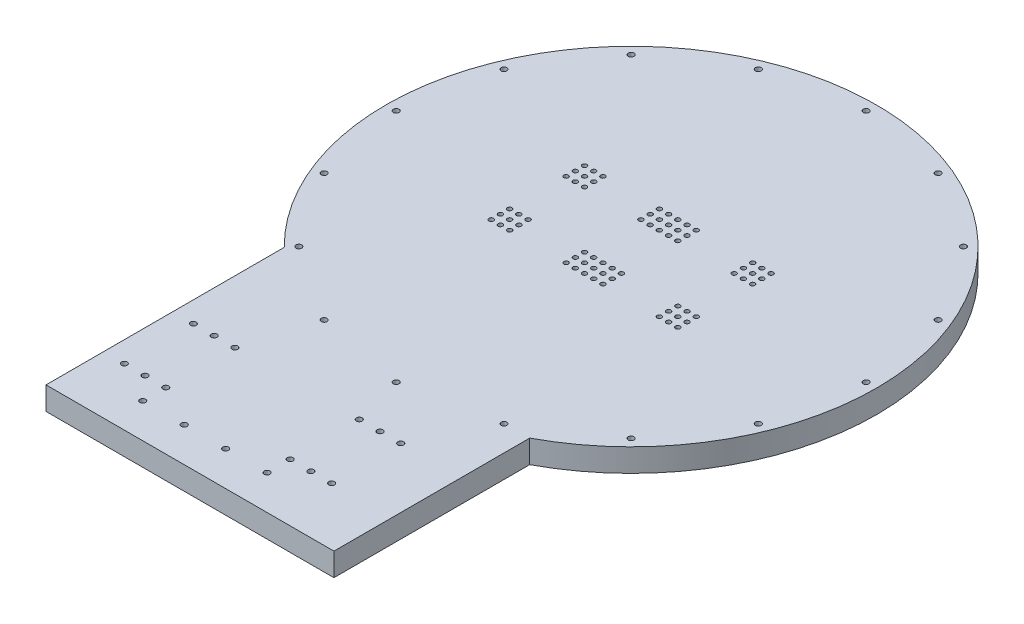
SolidWorks part; units mm, degrees
ref_plane "前视基准面" through (0, 0, 0) normal (0, 0, 1) x (1, 0, 0)
ref_plane "上视基准面" through (0, 0, 0) normal (0, 1, 0) x (1, 0, 0)
ref_plane "右视基准面" through (0, 0, 0) normal (1, 0, 0) x (0, 0, -1)
sketch "草图1" plane through (0, 0, 0) normal (0, 1, 0) x (1, 0, 0)
  circle A0 centre (0, 0) radius 195
  dimension "D1" = 390
extrude "凸台-拉伸1" add sketch "草图1" along normal blind 20
sketch "草图2" plane through (0, 20, 0) normal (0, 1, 0) x (1, 0, 0)
  line L0 (0, 0) -> (0, 15)
  line L1 (0, 15) -> (8, 15)
  line L2 (8, 15) -> (-8, 15)
  line L3 (-8, 15) -> (-8, 0)
  line L4 (8, 15) -> (8, 0)
  line L5 (-8, 32.5) -> (-8, -32.5)
  line L6 (-169.2909, 0) -> (169.2909, 0)
  line L7 (-8, 32.5) -> (-73, 32.5)
  line L8 (-8, 32.5) -> (-8, -32.5)
  line L9 (8, -32.5) -> (8, 32.5)
  line L10 (-8, -32.5) -> (-73, -32.5)
  line L11 (8, 32.5) -> (73, 32.5)
  line L12 (8, 32.5) -> (8, -32.5)
  line L13 (8, -32.5) -> (73, -32.5)
  line L14 (73, 32.5) -> (73, -32.5)
  line L15 (-73, 32.5) -> (-73, -32.5)
  line L16 (0, 158.5873) -> (0, -158.5873)
  circle A0 centre (-73, 32.5) radius 2
  circle A1 centre (-8, 32.5) radius 2
  circle A2 centre (-73, -32.5) radius 2
  circle A3 centre (-8, -32.5) radius 2
  circle A4 centre (8, 32.5) radius 2
  circle A5 centre (8, -32.5) radius 2
  circle A6 centre (73, -32.5) radius 2
  circle A7 centre (73, 32.5) radius 2
  point P8 (-8, 15)
  point P14 (8, 0)
  point P16 (-8, 0)
  point P29 (0, 0)
  point P32 (0, 0)
  dimension "D9" = 4
  dimension "D10" = 4
  dimension "D11" = 4
  dimension "D12" = 4
  dimension "D13" = 65
  dimension "D14" = 4
  dimension "D15" = 4
  dimension "D16" = 4
  dimension "D17" = 4
  dimension "D1" = 15
  dimension "D2" = 8
  dimension "D3" = 16
  dimension "D4" = 15
  dimension "D5" = 65
  dimension "D6" = 15
  dimension "D7" = 65
  dimension "D8" = 65
hole_wizard "M4 螺纹孔1" positions "3D草图2" profile "草图25" tap size "M4" standard "ISO"
sketch3d "3D草图2"
  point P0 (-73, 20, -32.5)
  point P3 (-73, 20, 32.5)
  point P6 (-8, 20, 32.5)
  point P9 (8, 20, 32.5)
  point P12 (-8, 20, -32.5)
  point P15 (8, 20, -32.5)
  point P18 (73, 20, -32.5)
  point P21 (73, 20, 32.5)
sketch "草图25" plane through (-73, 20, -32.5) normal (1, 0, 0) x (0, 0, 1)
  line L0 (0, 0) -> (0, 11.2017)
  line L1 (0, 11.2017) -> (2, 10)
  line L2 (2, 10) -> (2, 0)
  line L5 (2, 0) -> (0, 0)
  line L10 (0, 11.2017) -> (-2, 10) construction
  line L11 (0, -6.35) -> (0, 107.95) construction
  dimension "螺纹孔钻头直径" = 4
  dimension "螺纹孔钻头深度" = 10
  dimension "导头角度" = 118
cosmetic thread "孔螺蚊线2" parameters "D1"=9.5, "D2"=4
cosmetic thread "孔螺蚊线3" parameters "D1"=9.5, "D2"=4
cosmetic thread "孔螺蚊线4" parameters "D1"=9.5, "D2"=4
cosmetic thread "孔螺蚊线5" parameters "D1"=9.5, "D2"=4
cosmetic thread "孔螺蚊线6" parameters "D1"=9.5, "D2"=4
cosmetic thread "孔螺蚊线7" parameters "D1"=9.5, "D2"=4
cosmetic thread "孔螺蚊线8" parameters "D1"=9.5, "D2"=4
cosmetic thread "孔螺蚊线9" parameters "D1"=9.5, "D2"=4
pattern_linear "阵列(线性)2" count 2 spacing 8 along (-1, 0, 0) count 2 spacing 8 along (0, 0, 1) of "M4 螺纹孔1"
pattern_linear "阵列(线性)3" count 2 spacing 8 along (1, 0, 0) count 2 spacing 8 along (0, 0, -1) of "M4 螺纹孔1"
pattern_linear "阵列(线性)4" count 2 spacing 8 along (1, 0, 0) count 2 spacing 8 along (0, 0, 1) of "M4 螺纹孔1"
pattern_linear "阵列(线性)5" count 2 spacing 8 along (-1, 0, 0) count 2 spacing 8 along (0, 0, -1) of "M4 螺纹孔1"
sketch "草图3" plane through (0, 20, 0) normal (0, 1, 0) x (1, 0, 0)
  circle A0 centre (0, 0) radius 213
  circle A1 centre (0, 0) radius 204
  circle A2 centre (0, 204) radius 3
  circle A3 centre (78.0674, 188.4714) radius 3
  circle A4 centre (0, 0) radius 204
  circle A5 centre (144.2498, 144.2498) radius 3
  circle A6 centre (0, 0) radius 204
  circle A7 centre (188.4714, 78.0674) radius 3
  circle A8 centre (0, 0) radius 204
  circle A9 centre (204, 0) radius 3
  circle A10 centre (0, 0) radius 204
  circle A11 centre (188.4714, -78.0674) radius 3
  circle A12 centre (0, 0) radius 204
  circle A13 centre (144.2498, -144.2498) radius 3
  circle A14 centre (0, 0) radius 204
  circle A15 centre (78.0674, -188.4714) radius 3
  circle A16 centre (0, 0) radius 204
  circle A17 centre (0, -204) radius 3
  circle A18 centre (0, 0) radius 204
  circle A19 centre (-78.0674, -188.4714) radius 3
  circle A20 centre (0, 0) radius 204
  circle A21 centre (-144.2498, -144.2498) radius 3
  circle A22 centre (0, 0) radius 204
  circle A23 centre (-188.4714, -78.0674) radius 3
  circle A24 centre (0, 0) radius 204
  circle A25 centre (-204, 0) radius 3
  circle A26 centre (0, 0) radius 204
  circle A27 centre (-188.4714, 78.0674) radius 3
  circle A28 centre (0, 0) radius 204
  circle A29 centre (-144.2498, 144.2498) radius 3
  circle A30 centre (0, 0) radius 204
  circle A31 centre (-78.0674, 188.4714) radius 3
  circle A32 centre (0, 0) radius 204
  circle A33 centre (0, 0) radius 195
  circle A34 centre (0, 0) radius 204
  circle A36 centre (0, 0) radius 204
  circle A38 centre (0, 0) radius 204
  circle A40 centre (0, 0) radius 204
  circle A42 centre (0, 0) radius 204
  circle A44 centre (0, 0) radius 204
  circle A46 centre (0, 0) radius 204
  circle A48 centre (0, 0) radius 204
  circle A50 centre (0, 0) radius 204
  circle A52 centre (0, 0) radius 204
  circle A54 centre (0, 0) radius 204
  circle A56 centre (0, 0) radius 204
  circle A58 centre (0, 0) radius 204
  circle A60 centre (0, 0) radius 204
  circle A62 centre (0, 0) radius 204
  circle A64 centre (0, 0) radius 204
  circle A66 centre (0, 0) radius 204
  circle A68 centre (0, 0) radius 204
  circle A70 centre (0, 0) radius 204
  circle A72 centre (0, 0) radius 204
  circle A73 centre (35.4242, 200.9008) radius 3 [skipped]
  circle A74 centre (69.7721, 191.6973) radius 3 [skipped]
  circle A75 centre (102, 176.6692) radius 3 [skipped]
  circle A76 centre (131.1287, 156.2731) radius 3 [skipped]
  circle A77 centre (156.2731, 131.1287) radius 3 [skipped]
  circle A78 centre (176.6692, 102) radius 3 [skipped]
  circle A79 centre (-35.4242, -200.9008) radius 3 [skipped]
  circle A80 centre (0, -204) radius 3 [skipped]
  circle A81 centre (35.4242, -200.9008) radius 3 [skipped]
  circle A82 centre (69.7721, -191.6973) radius 3 [skipped]
  circle A83 centre (102, -176.6692) radius 3 [skipped]
  circle A84 centre (131.1287, -156.2731) radius 3 [skipped]
  circle A85 centre (156.2731, -131.1287) radius 3 [skipped]
  circle A86 centre (176.6692, -102) radius 3 [skipped]
  circle A87 centre (191.6973, 69.7721) radius 3 [skipped]
  circle A88 centre (200.9008, 35.4242) radius 3 [skipped]
  circle A89 centre (204, 0) radius 3 [skipped]
  circle A90 centre (200.9008, -35.4242) radius 3 [skipped]
  circle A91 centre (191.6973, -69.7721) radius 3 [skipped]
  circle A92 centre (-69.7721, -191.6973) radius 3 [skipped]
  circle A93 centre (-102, -176.6692) radius 3 [skipped]
  circle A94 centre (-131.1287, -156.2731) radius 3 [skipped]
  circle A95 centre (-156.2731, -131.1287) radius 3 [skipped]
  circle A96 centre (-176.6692, -102) radius 3 [skipped]
  circle A97 centre (-191.6973, -69.7721) radius 3 [skipped]
  circle A98 centre (-200.9008, -35.4242) radius 3 [skipped]
  circle A99 centre (-204, 0) radius 3 [skipped]
  circle A100 centre (-200.9008, 35.4242) radius 3 [skipped]
  circle A101 centre (-191.6973, 69.7721) radius 3 [skipped]
  circle A102 centre (-176.6692, 102) radius 3 [skipped]
  circle A103 centre (-156.2731, 131.1287) radius 3 [skipped]
  circle A104 centre (-131.1287, 156.2731) radius 3 [skipped]
  circle A105 centre (-102, 176.6692) radius 3 [skipped]
  circle A106 centre (-69.7721, 191.6973) radius 3 [skipped]
  circle A107 centre (-35.4242, 200.9008) radius 3 [skipped]
  point P55 (0, 0)
  point P114 (0, 0)
  dimension "D1" = 426
  dimension "D2" = 408
  dimension "D3" = 6
  dimension "D4" = 36
  dimension "D5" = 16
extrude "凸台-拉伸2" add sketch "草图3" against normal blind 20
sketch "草图9" plane through (0, 0, 0) normal (0, -1, 0) x (1, 0, 0)
  line L5 (0, 0) -> (0, 262.5812) construction
  line L6 (-100, 210.4048) -> (100, 210.4048) construction
  line L7 (100, 210.4048) -> (100, 188.0665) construction
  line L8 (100, 188.0665) -> (100, 338.0665)
  line L9 (100, 338.0665) -> (-100, 338.0665)
  line L10 (-100, 338.0665) -> (-100, 188.0665)
  arc A0 (-100, 188.0665) -> (100, 188.0665) centre (0, -24.5952) cw
  circle A1 centre (0, 0) radius 213 construction
  point P7 (-209.55, 0)
  point P18 (0, 210.4048)
  dimension "D1" = 235
  dimension "D4" = 200
  dimension "D5" = 150
  dimension "D6" = 150
  dimension "D7" = 200
extrude "凸台-拉伸3" add sketch "草图9" against normal blind 20
sketch "草图14" plane through (0, 20, 0) normal (0, 1, 0) x (1, 0, 0)
  line L0 (-100, -338.0665) -> (-150, -338.0665)
  line L1 (-150, -338.0665) -> (-150, -151.225)
  line L2 (-100, -338.0665) -> (-100, -188.0665)
  arc A0 (100, -188.0665) -> (-100, -188.0665) centre (0, 0) ccw construction
  arc A1 (-100, -188.0665) -> (-150, -151.225) centre (13.1778, 17.8845) cw
  dimension "D2" = 235
  dimension "D1" = 50
extrude "凸台-拉伸4" add sketch "草图14" against normal blind 20
sketch "草图23" plane through (0, 0, 338.0665) normal (0, 0, 1) x (1, 0, 0)
  line L1 (-150, 20) -> (100, 20)
  line L2 (-150, 20) -> (-150, 0)
  line L3 (-150, 0) -> (100, 0)
  line L4 (100, 20) -> (100, 0)
extrude "凸台-拉伸5" add sketch "草图23" along normal blind 20
sketch "草图21" plane through (0, 20, 0) normal (0, 1, 0) x (1, 0, 0)
  line L0 (0, 0) -> (0, -252)
  dimension "D1" = 252
sketch "草图22" plane through (0, 20, 0) normal (0, 1, 0) x (1, 0, 0)
  line L0 (0, -252) -> (-102, -252)
  line L1 (0, -252) -> (12, -252)
  line L2 (17.5, -347) -> (-107.5, -347)
  line L3 (-102, -252) -> (12, -252)
  line L4 (-102, -252) -> (-102, -347)
  line L5 (-102, -347) -> (12, -347)
  line L6 (12, -252) -> (12, -347)
  line L7 (17.5, -347) -> (17.5, -362)
  line L8 (17.5, -362) -> (67.5, -362)
  circle A0 centre (67.5, -362) radius 3
  circle A1 centre (42.5, -362) radius 3
  circle A2 centre (17.5, -362) radius 3
  circle A3 centre (-7.5, -362) radius 3
  circle A4 centre (-32.5, -362) radius 3
  circle A5 centre (-57.5, -362) radius 3
  circle A6 centre (-82.5, -362) radius 3
  circle A7 centre (-107.5, -362) radius 3
  circle A8 centre (-132.5, -362) radius 3
  circle A9 centre (42.5, -337) radius 3
  circle A10 centre (17.5, -337) radius 3
  circle A11 centre (-7.5, -337) radius 3
  circle A12 centre (-32.5, -337) radius 3
  circle A13 centre (-57.5, -337) radius 3
  circle A14 centre (-82.5, -337) radius 3
  circle A15 centre (-107.5, -337) radius 3
  circle A16 centre (-132.5, -337) radius 3
  circle A17 centre (42.5, -312) radius 3
  circle A18 centre (17.5, -312) radius 3
  circle A19 centre (-7.5, -312) radius 3
  circle A20 centre (-32.5, -312) radius 3
  circle A21 centre (-57.5, -312) radius 3
  circle A22 centre (-82.5, -312) radius 3
  circle A23 centre (-107.5, -312) radius 3
  circle A24 centre (-132.5, -312) radius 3
  circle A25 centre (42.5, -287) radius 3
  circle A26 centre (17.5, -287) radius 3
  circle A27 centre (-7.5, -287) radius 3
  circle A28 centre (-32.5, -287) radius 3
  circle A29 centre (-57.5, -287) radius 3
  circle A30 centre (-82.5, -287) radius 3
  circle A31 centre (-107.5, -287) radius 3
  circle A32 centre (-132.5, -287) radius 3
  circle A33 centre (42.5, -262) radius 3
  circle A34 centre (17.5, -262) radius 3
  circle A35 centre (-7.5, -262) radius 3
  circle A36 centre (-32.5, -262) radius 3
  circle A37 centre (-57.5, -262) radius 3
  circle A38 centre (-82.5, -262) radius 3
  circle A39 centre (-107.5, -262) radius 3
  circle A40 centre (-132.5, -262) radius 3
  circle A41 centre (42.5, -237) radius 3
  circle A42 centre (17.5, -237) radius 3
  circle A43 centre (-7.5, -237) radius 3
  circle A44 centre (-32.5, -237) radius 3
  circle A45 centre (-57.5, -237) radius 3
  circle A46 centre (-82.5, -237) radius 3
  circle A47 centre (-107.5, -237) radius 3
  circle A48 centre (-132.5, -237) radius 3
  circle A49 centre (67.5, -337) radius 3
  circle A50 centre (67.5, -312) radius 3
  circle A51 centre (67.5, -287) radius 3
  circle A52 centre (67.5, -262) radius 3
  circle A53 centre (67.5, -237) radius 3
  point P9 (-45, -347)
  dimension "D6" = 50
  dimension "D7" = 6
  dimension "D1" = 102
  dimension "D2" = 12
  dimension "D3" = 95
  dimension "D4" = 125
  dimension "D5" = 15
  dimension "D8" = 9
  dimension "D9" = 6
sketch "草图31" plane through (0, 20, 0) normal (0, 1, 0) x (1, 0, 0)
  line L0 (0, 0) -> (0, 204)
  circle A0 centre (0, 0) radius 204
  dimension "D1" = 408
hole_wizard "M6 螺纹孔3" positions "3D草图4" profile "草图32" tap size "M6" standard "ISO" end condition through all
sketch3d "3D草图4"
  point P0 (0, 20, -204)
sketch "草图32" plane through (0, 20, -204) normal (1, 0, 0) x (0, 0, 1)
  line L0 (0, 0) -> (0, 20)
  line L1 (0, 20) -> (2.5, 20)
  line L2 (2.5, 20) -> (2.5, 0)
  line L5 (2.5, 0) -> (0, 0)
  line L11 (0, -6.35) -> (0, 107.95) construction
  dimension "通孔螺纹孔钻头直径" = 5
  dimension "通孔螺纹孔钻头深度" = 20
cosmetic thread "孔螺蚊线11" parameters "D2"=6
pattern_circular "阵列(圆周)2" count 16 over 360 about axis through (0, 0, 0) along (0, 1, 0) of "M6 螺纹孔3"
sketch "草图33" plane through (0, 20, 0) normal (0, 1, 0) x (1, 0, 0)
  line L0 (-150, -358.0665) -> (-114, -358.0665)
  line L1 (100, -358.0665) -> (-150, -358.0665) construction
  line L2 (-114, -358.0665) -> (-114, -308.0665)
  dimension "D1" = 36
  dimension "D2" = 50
hole_wizard "M6 螺纹孔4" positions "3D草图5" profile "草图34" tap size "M6" standard "ISO" end condition through all
sketch3d "3D草图5"
  point P0 (-114, 20, 308.0665)
sketch "草图34" plane through (-114, 20, 308.0665) normal (1, 0, 0) x (0, 0, 1)
  line L0 (0, 0) -> (0, 20)
  line L1 (0, 20) -> (2.5, 20)
  line L2 (2.5, 20) -> (2.5, 0)
  line L5 (2.5, 0) -> (0, 0)
  line L11 (0, -6.35) -> (0, 107.95) construction
  dimension "通孔螺纹孔钻头直径" = 5
  dimension "通孔螺纹孔钻头深度" = 20
cosmetic thread "孔螺蚊线12" parameters "D2"=6
pattern_linear "阵列(线性)7" count 2 spacing 60 along (0, 0, -1) count 2 spacing 144 along (1, 0, 0) of "M6 螺纹孔4"
sketch "草图35" plane through (0, 20, 0) normal (0, 1, 0) x (1, 0, 0)
  line L0 (-114, -308.0665) -> (-114, -328.0665)
  line L1 (-114, -328.0665) -> (-60, -328.0665)
  dimension "D1" = 20
  dimension "D2" = 54
hole_wizard "M6 螺纹孔5" positions "3D草图6" profile "草图36" tap size "M6" standard "ISO" end condition through all
sketch3d "3D草图6"
  point P0 (-60, 20, 328.0665)
sketch "草图36" plane through (-60, 20, 328.0665) normal (1, 0, 0) x (0, 0, 1)
  line L0 (0, 0) -> (0, 20)
  line L1 (0, 20) -> (2.5, 20)
  line L2 (2.5, 20) -> (2.5, 0)
  line L5 (2.5, 0) -> (0, 0)
  line L11 (0, -6.35) -> (0, 107.95) construction
  dimension "通孔螺纹孔钻头直径" = 5
  dimension "通孔螺纹孔钻头深度" = 20
cosmetic thread "孔螺蚊线13" parameters "D2"=6
pattern_linear "阵列(线性)8" count 3 spacing 36 along (1, 0, 0) of "M6 螺纹孔5"
pattern_linear "阵列(线性)9" count 2 spacing 18 along (1, 0, 0) of "阵列(线性)7", "M6 螺纹孔4"
pattern_linear "阵列(线性)10" count 2 spacing 18 along (-1, 0, 0) of "阵列(线性)7", "M6 螺纹孔4"
pattern_linear "阵列(线性)11" count 2 spacing 36 along (-1, 0, 0) of "M6 螺纹孔5"
sketch "草图37" plane through (0, 20, 0) normal (0, 1, 0) x (1, 0, 0)
  arc A0 (100, -188.0665) -> (-150, -151.225) centre (0, 0) ccw construction
  arc A1 (100, -188.0665) -> (-150, -151.225) centre (0, 0) ccw
sketch "草图39" plane through (0, 0, 0) normal (0, -1, 0) x (1, 0, 0)
  arc A4 (-150, 151.225) -> (100, 188.0665) centre (0, 0) ccw construction
  arc A5 (-150, 151.225) -> (100, 188.0665) centre (0, 0) ccw
  circle A8 centre (-81, 24.5) radius 2 construction
